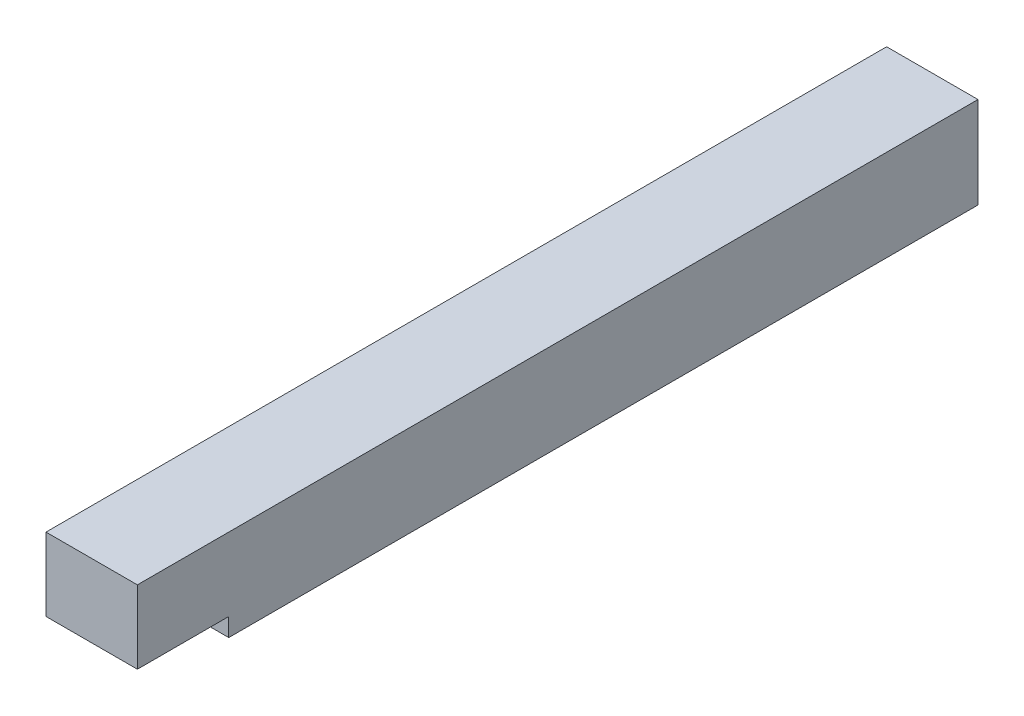
SolidWorks part; units mm, degrees
ref_plane "Plan de face" through (0, 0, 0) normal (0, 0, 1) x (1, 0, 0)
ref_plane "Plan de dessus" through (0, 0, 0) normal (0, 1, 0) x (1, 0, 0)
ref_plane "Plan de droite" through (0, 0, 0) normal (1, 0, 0) x (0, 0, -1)
sketch "Esquisse1" plane through (0, 0, 0) normal (0, 0, 1) x (1, 0, 0)
  line L1 (0, 0) -> (10, 0)
  line L2 (0, 0) -> (0, 10)
  line L3 (0, 10) -> (10, 10)
  line L4 (10, 0) -> (10, 10)
  dimension "D1" = 10
  dimension "D2" = 10
extrude "Boss.-Extru.1" add sketch "Esquisse1" along normal blind 92
sketch "Esquisse2" plane through (0, 0, 0) normal (0, -1, 0) x (1, 0, 0)
  line L0 (0, 92) -> (0, 0) construction
  line L1 (10, 92) -> (0, 92)
  line L2 (10, 92) -> (10, 82)
  line L3 (10, 82) -> (0, 82)
  line L4 (0, 92) -> (0, 82)
  dimension "D1" = 10
extrude "Enlèv. mat.-Extru.1" cut sketch "Esquisse2" against normal blind 2
